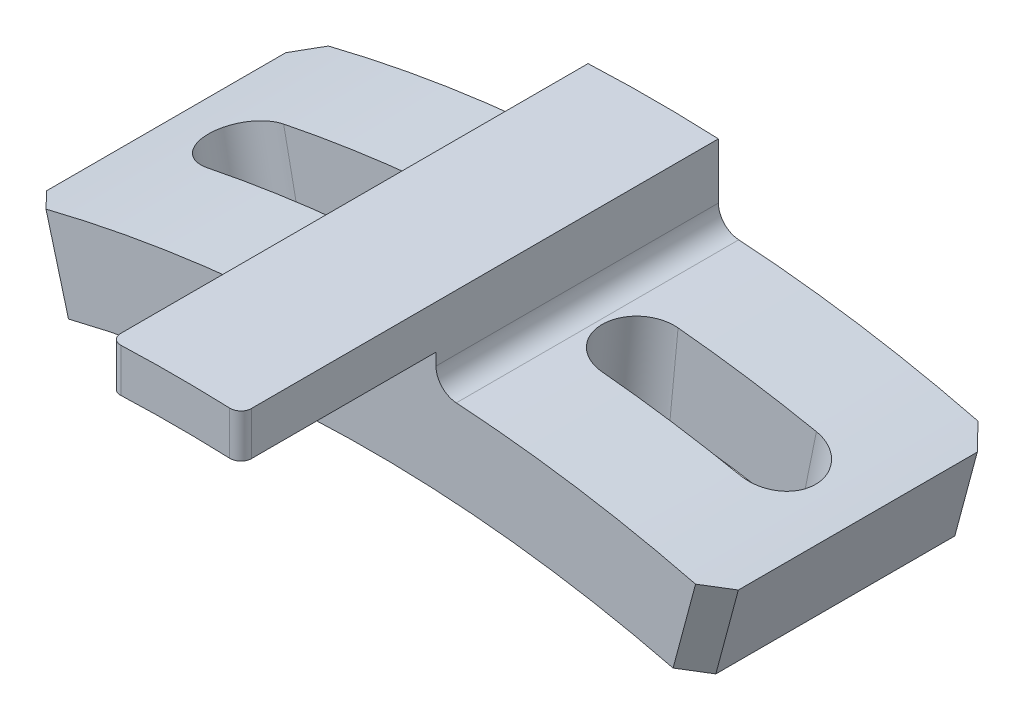
SolidWorks part; units mm, degrees
material "PETG"
ref_plane "Спереди" through (0, 0, 0) normal (0, 0, 1) x (1, 0, 0)
ref_plane "Сверху" through (0, 0, 0) normal (0, 1, 0) x (1, 0, 0)
ref_plane "Справа" through (0, 0, 0) normal (1, 0, 0) x (0, 0, -1)
sketch "Эскиз1" plane through (0, 0, 0) normal (0, 0, 1) x (1, 0, 0)
  line L0 (14.8821, 55.5407) -> (15.9174, 59.4044)
  line L1 (-14.8821, 55.5407) -> (-15.9174, 59.4044)
  line L2 (0, 0) -> (0, 84.5239) construction
  line L3 (-3, 64.9307) -> (-3, 61.4268)
  line L4 (3, 64.9307) -> (3, 61.4268)
  arc A0 (14.8821, 55.5407) -> (-14.8821, 55.5407) centre (0, 0) ccw
  arc A1 (3, 64.9307) -> (-3, 64.9307) centre (0, 0) ccw
  arc A2 (15.9174, 59.4044) -> (3, 61.4268) centre (0, 0) ccw
  circle A3 centre (0, 0) radius 65 construction
  circle A4 centre (0, 0) radius 57.5 construction
  arc A5 (-3, 61.4268) -> (-15.9174, 59.4044) centre (0, 0) ccw
  arc A7 (15.9174, 59.4044) -> (-15.9174, 59.4044) centre (0, 0) ccw construction
  point P6 (59.769, 18.2732)
  point P7 (70, 0)
  dimension "D1" = 115
  dimension "D4" = 4
  dimension "D3" = 15
  dimension "D5" = 6
  dimension "D2" = 7.5
extrude "Бобышка-Вытянуть1" add sketch "Эскиз1" along normal mid plane 13
sketch "Эскиз2" plane through (0, 0, 6.5) normal (0, 0, 1) x (1, 0, 0)
  line L0 (3, 61.4268) -> (3, 64.9307) construction
  line L1 (-3, 64.9307) -> (-3, 61.4268) construction
  line L2 (3, 62.9285) -> (3, 64.9307)
  line L3 (-3, 64.9307) -> (-3, 62.9285)
  arc A0 (3, 64.9307) -> (-3, 64.9307) centre (0, 0) ccw construction
  arc A1 (3, 64.9307) -> (-3, 64.9307) centre (0, 0) ccw
  arc A2 (2.9077, 62.9329) -> (-2.9077, 62.9329) centre (0, 0) ccw construction
  arc A6 (3, 62.9285) -> (-3, 62.9285) centre (0, 0) ccw
  dimension "D1" = 2
extrude "Бобышка-Вытянуть2" add sketch "Эскиз2" along normal blind 9
sketch "Эскиз4" plane through (0, 0, 0) normal (0, 0, 1) x (1, 0, 0)
  line L0 (0, 0) -> (12.2611, 60.2654) construction
  line L1 (15.6706, 68.2458) -> (11.6833, 48.6473)
  line L4 (11.6833, 48.6473) -> (9.9684, 48.9962)
  line L5 (15.6706, 68.2458) -> (13.9558, 68.5947)
  line L6 (9.9684, 48.9962) -> (13.9558, 68.5947)
  line L7 (0, 0) -> (0, 57.5) construction
  arc A0 (15.9174, 59.4044) -> (3, 61.4268) centre (0, 0) ccw construction
  arc A1 (14.8821, 55.5407) -> (-14.8821, 55.5407) centre (0, 0) ccw construction
  dimension "D1" = 3.5
  dimension "D2" = 11.5
  dimension "D3" = 50
  dimension "D4" = 20
revolve "Вырез-Повернуть1" cut sketch "Эскиз4" angle 360 about L0
pattern_circular "Круговой массив1" count 2 every 6 about axis through (0, 0, 6.5) along (0, 0, -1) of "Вырез-Повернуть1"
sketch "Эскиз6" plane through (0, 0, 0) normal (0, 0, 1) x (1, 0, 0)
  line L0 (5.5111, 57.2353) -> (5.8945, 61.2169)
  line L1 (11.4637, 56.3457) -> (12.2611, 60.2654)
  arc A0 (14.8821, 55.5407) -> (-14.8821, 55.5407) centre (0, 0) ccw construction
  arc A1 (15.9174, 59.4044) -> (3, 61.4268) centre (0, 0) ccw construction
  arc A2 (11.4637, 56.3457) -> (5.5111, 57.2353) centre (0, 0) ccw
  arc A3 (12.2611, 60.2654) -> (5.8945, 61.2169) centre (0, 0) ccw
  arc A8 (7.2505, 57.041) -> (3.7666, 57.3765) centre (0, 0) ccw construction
  arc A10 (7.6341, 61.0243) -> (4.1502, 61.3598) centre (0, 0) ccw construction
  arc A11 (13.1732, 55.9707) -> (9.7435, 56.6685) centre (0, 0) ccw construction
  arc A12 (13.971, 59.8921) -> (10.5413, 60.5899) centre (0, 0) ccw construction
extrude "Вырез-Вытянуть2" cut sketch "Эскиз6" against normal mid plane 3.5
mirror "Зеркальное отражение1" about plane through (0, 0, 0) normal (1, 0, 0) of "Вырез-Вытянуть2", "Круговой массив1", "Вырез-Повернуть1"
fillet "Скругление1" radius 1 2 edges at (-3, 61.4268, 0) (3, 61.4268, 0)
chamfer "Фаска1" distance 1 angle 45 4 edges at (15.3997, 57.4726, 6.5) (-15.3997, 57.4726, 6.5) (-15.3997, 57.4726, -6.5) (15.3997, 57.4726, -6.5)
fillet "Скругление2" radius 0.5 2 edges at (3, 63.9296, 15.5) (-3, 63.9296, 15.5)
